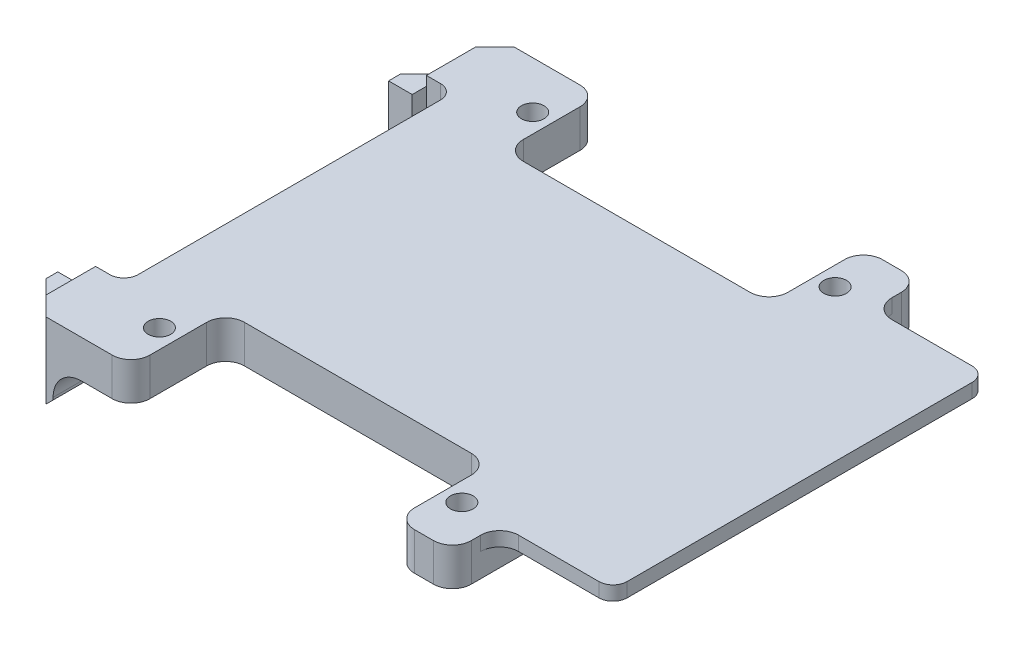
SolidWorks part; units mm, degrees
ref_plane "Front Plane" through (0, 0, 0) normal (0, 0, 1) x (1, 0, 0)
ref_plane "Top Plane" through (0, 0, 0) normal (0, 1, 0) x (1, 0, 0)
ref_plane "Right Plane" through (0, 0, 0) normal (1, 0, 0) x (0, 0, -1)
sketch "Sketch1" plane through (0, 0, 0) normal (0, 0, 1) x (1, 0, 0)
  line L0 (0, 57.0166) -> (0, -12.2536) construction
  line L1 (-45.9137, 0) -> (51.379, 0) construction
  line L2 (-25, 24) -> (32, 24)
  line L3 (-26.5, 17) -> (-25, 17)
  line L4 (-25, 17) -> (-25, 24)
  line L5 (-26.5, 17) -> (-26.5, 15.5)
  line L6 (-26.5, 15.5) -> (-23.5, 15.5)
  line L7 (-23.5, 15.5) -> (-23.5, 22.5)
  line L8 (-23.5, 22.5) -> (32, 22.5)
  line L9 (32, 22.5) -> (32, 24)
  dimension "D1" = 17
  dimension "D2" = 25
  dimension "D3" = 24
  dimension "D4" = 1.5
  dimension "D5" = 1.5
  dimension "D6" = 1.5
  dimension "D7" = 1.5
  dimension "D8" = 32
extrude "Boss-Extrude1" add sketch "Sketch1" along normal mid plane 39.5
sketch "Sketch2" plane through (0, 22.5, 0) normal (0, -1, 0) x (1, 0, 0)
  line L0 (0, -28.7784) -> (0, 29.8663) construction
  line L1 (-38.3762, 0) -> (49.937, 0) construction
  line L2 (-14, 19.75) -> (-14, 14.75)
  line L3 (-23.5, 19.75) -> (32, 19.75) construction
  line L4 (-14, 14.75) -> (14, 14.75)
  line L5 (-14, 19.75) -> (14, 19.75)
  line L6 (14, 19.75) -> (14, 14.75)
  line L7 (14, -19.75) -> (14, -14.75)
  line L8 (-14, -19.75) -> (14, -19.75)
  line L9 (-14, -14.75) -> (14, -14.75)
  line L10 (-14, -19.75) -> (-14, -14.75)
  point P9 (0, -14.75)
  point P12 (0, 19.75)
  point P13 (0, 14.75)
  point P14 (0, -19.75)
  dimension "D1" = 5
  dimension "D2" = 28
extrude "Cut-Extrude1" cut sketch "Sketch2" against normal through all
sketch "Sketch3" plane through (0, 24, 0) normal (0, 1, 0) x (1, 0, 0)
  line L0 (-37.8503, 0) -> (59.1934, 0) construction
  line L1 (0, -32.5682) -> (0, 30.7465) construction
  line L2 (-14, 19.75) -> (-20, 19.75)
  line L3 (-14, 19.75) -> (-25, 19.75) construction
  line L4 (-20, 19.75) -> (-20, 24.75)
  line L5 (-20, 24.75) -> (-14, 24.75)
  line L6 (-14, 24.75) -> (-14, 19.75)
  line L7 (14, 24.75) -> (14, 19.75)
  line L8 (20, 24.75) -> (14, 24.75)
  line L9 (20, 19.75) -> (20, 24.75)
  line L10 (14, 19.75) -> (20, 19.75)
  line L11 (14, -19.75) -> (20, -19.75)
  line L12 (20, -19.75) -> (20, -24.75)
  line L13 (20, -24.75) -> (14, -24.75)
  line L14 (14, -24.75) -> (14, -19.75)
  line L15 (-14, -24.75) -> (-14, -19.75)
  line L16 (-20, -24.75) -> (-14, -24.75)
  line L17 (-20, -19.75) -> (-20, -24.75)
  line L18 (-14, -19.75) -> (-20, -19.75)
  line L19 (17, 24.75) -> (17, 19.75) construction
  circle A0 centre (17, 22.25) radius 1 construction
  circle A1 centre (17, -22.25) radius 1 construction
  circle A2 centre (-17, 22.25) radius 1 construction
  circle A3 centre (-17, -22.25) radius 1 construction
  line M8 (14, -19.75) -> (32, -19.75)
  line M10 (32, 19.75) -> (14, 19.75)
  line M14 (-14, 19.75) -> (-25, 19.75)
  line M16 (-25, -19.75) -> (-14, -19.75)
  dimension "D3" = 2
  dimension "D1" = 5
  dimension "D2" = 6
extrude "Boss-Extrude2" add sketch "Sketch3" against normal blind 4 contours L14 L13 L12 A1 M8 | L17 L16 L15 A3 M16 | L9 L8 L7 A0 M10 | L6 L5 L4 A2 M14
sketch "Sketch4" plane through (0, 22.5, 0) normal (0, -1, 0) x (1, 0, 0)
  line L0 (0, 35.1625) -> (0, -33.0766) construction
  line L1 (-40.0719, 0) -> (51.9068, 0) construction
  line L2 (-20, 20.25) -> (-20, 17.25)
  line L4 (-20, 17.25) -> (-17.5, 17.25)
  line L5 (-17.5, 17.25) -> (-17.5, 20.25)
  line L6 (-17.5, 20.25) -> (-20, 20.25)
  line L7 (17.5, 20.25) -> (20, 20.25)
  line L8 (17.5, 17.25) -> (17.5, 20.25)
  line L9 (20, 17.25) -> (17.5, 17.25)
  line L10 (20, 20.25) -> (20, 17.25)
  line L11 (20, -20.25) -> (20, -17.25)
  line L12 (20, -17.25) -> (17.5, -17.25)
  line L13 (17.5, -17.25) -> (17.5, -20.25)
  line L14 (17.5, -20.25) -> (20, -20.25)
  line L15 (-17.5, -20.25) -> (-20, -20.25)
  line L16 (-17.5, -17.25) -> (-17.5, -20.25)
  line L17 (-20, -17.25) -> (-17.5, -17.25)
  line L18 (-20, -20.25) -> (-20, -17.25)
  line L19 (-23.5, 19.75) -> (-20, 19.75) construction
  line L20 (-14, 24.75) -> (-14, 14.75) construction
  dimension "D1" = 0.5
  dimension "D2" = 3
  dimension "D3" = 2.5
  dimension "D4" = 6
extrude "Boss-Extrude3" [suppressed] add sketch "Sketch4" along normal blind 4
chamfer "Chamfer1" [suppressed] distance 4 angle 45
sketch "Sketch6" plane through (0, 0, -24.75) normal (0, 0, -1) x (-1, 0, 0)
  line L0 (20, 24) -> (25, 24)
  line L1 (20, 20) -> (20, 24) construction
  line L2 (25, 24) -> (25, 15.5)
  line L3 (26.5, 15.5) -> (23.5, 15.5) construction
  line L4 (25, 15.5) -> (23.5, 15.5)
  line L5 (23.5, 15.5) -> (22.25, 16.75)
  line L7 (20, 20) -> (20, 24)
  line L8 (20, 20) -> (19.25, 20)
  line L9 (22.25, 17) -> (22.25, 16.75)
  line L10 (23.5, 15.5) -> (23.5, 22.5) construction
  line L11 (20, 20) -> (14, 20) construction
  arc A0 (19.25, 20) -> (22.25, 17) centre (19.25, 17) cw
  dimension "D3" = 3
  dimension "D1" = 1.25
  dimension "D2" = 45
extrude "Boss-Extrude4" add sketch "Sketch6" against normal up to surface (5 mm away) up to face at (-23.75, 19.75, -19.75)
sketch "Sketch7" plane through (0, 0, 24.75) normal (0, 0, 1) x (1, 0, 0)
  line L0 (-20, 22.5) -> (-20, 24) construction
  line L2 (-20, 20) -> (-20, 24)
  line L4 (-20, 20) -> (-19.25, 20)
  line L7 (-14, 24) -> (-25, 24)
  line L8 (-14, 20) -> (-14, 24)
  line L9 (-20, 24) -> (-25, 24)
  line L10 (-22.25, 16.75) -> (-22.25, 17)
  line L11 (-23.5, 15.5) -> (-22.25, 16.75)
  line L12 (-25, 15.5) -> (-23.5, 15.5)
  line L13 (-25, 24) -> (-25, 15.5)
  line L17 (-22.25, 16.75) -> (-22.25, 17)
  line L18 (-23.5, 15.5) -> (-22.25, 16.75)
  line L19 (-25, 15.5) -> (-23.5, 15.5)
  line L20 (-25, 24) -> (-25, 15.5)
  line L21 (-19.25, 20) -> (-14, 20)
  arc A1 (-19.25, 20) -> (-22.25, 17) centre (-19.25, 17) ccw
  arc A2 (-19.25, 20) -> (-22.25, 17) centre (-19.25, 17) ccw
  dimension "D1" = 0
extrude "Boss-Extrude5" add sketch "Sketch7" against normal up to surface (5 mm away) up to face at (-23.75, 19.75, 19.75)
chamfer "Chamfer2" distance 2 angle 45 2 edges at (-25, 19.75, -24.75) (-25, 19.75, 24.75)
fillet "Fillet1" radius 2 12 edges at (20, 23.25, -19.75) (14, 22, -24.75) (20, 22, -24.75) (-14, 22, -24.75) (14, 22, 24.75) (20, 22, 24.75) (20, 23.25, 19.75) (-14, 22, 24.75) (-14, 23.25, 14.75) (14, 23.25, 14.75) (14, 23.25, -14.75) (-14, 23.25, -14.75)
sketch "Sketch8" plane through (0, 24, 0) normal (0, 1, 0) x (1, 0, 0)
  line L0 (-29.245, 0) -> (51.3108, 0) construction
  line L1 (-25, 17.5) -> (-22, 17.5)
  line L2 (-25, -19.75) -> (-25, 19.75) construction
  line L3 (-22, 17.5) -> (-22, -17.5)
  line L4 (-25, 17.5) -> (-25, -17.5) construction
  line L5 (-25, -22.75) -> (-25, 22.75) construction
  line L6 (-25, -17.5) -> (-22, -17.5)
  line L7 (-25, 17.5) -> (-26.8679, 17.5)
  line L8 (-26.8679, 17.5) -> (-26.8679, -17.5)
  line L9 (-25, -17.5) -> (-26.8679, -17.5)
  point P12 (-25, 0)
  point P13 (-22, 0)
  point P16 (-26.8679, 0)
  dimension "D1" = 3
  dimension "D2" = 35
extrude "Cut-Extrude3" cut sketch "Sketch8" against normal through all
sketch "Sketch9" plane through (0, 15.5, 0) normal (0, -1, 0) x (1, 0, 0)
  line L0 (-33.3175, 0) -> (50.3175, 0) construction
  line L1 (-25, 22.75) -> (-29, 18.75)
  line L2 (-29, 18.75) -> (-29, 17.5)
  line L3 (-29, 17.5) -> (-26.5, 17.5)
  line L4 (-26.5, 17.5) -> (-26.5, 20.5)
  line L5 (-26.5, 20.5) -> (-25, 20.5)
  line L6 (-25, 20.5) -> (-25, 22.75)
  line L7 (-23.5, 24.25) -> (-25, 22.75) construction
  line L8 (-25, -20.5) -> (-25, -22.75)
  line L9 (-26.5, -20.5) -> (-25, -20.5)
  line L10 (-26.5, -17.5) -> (-26.5, -20.5)
  line L11 (-29, -17.5) -> (-26.5, -17.5)
  line L12 (-29, -18.75) -> (-29, -17.5)
  line L13 (-25, -22.75) -> (-29, -18.75)
  dimension "D1" = 2.5
  dimension "D2" = 41
extrude "Boss-Extrude6" add sketch "Sketch9" against normal blind 6
fillet "Fillet2" radius 1.5 2 edges at (-25, 21.5, 21.625) (-25, 21.5, -21.625)
sketch "Sketch10" [suppressed] plane through (0, 20, 0) normal (0, -1, 0) x (1, 0, 0)
  line L0 (63.4148, 0) -> (-38.9985, 0) construction
  line L1 (17.5, 19.75) -> (17.5, 20.25)
  line L2 (17.5, 20.25) -> (-17.5, 20.25)
  line L3 (-17.5, 20.25) -> (-20, 20.25) construction
  line L4 (-17.5, 20.25) -> (-17.5, 19.75)
  line L5 (-17.5, 19.75) -> (-14, 19.75) construction
  line L6 (-17.5, 19.75) -> (17.5, 19.75)
  line L7 (-17.5, 17.25) -> (-17.5, 20.25) construction
  line L8 (-17.5, -19.75) -> (17.5, -19.75)
  line L9 (-17.5, -20.25) -> (-17.5, -19.75)
  line L10 (17.5, -20.25) -> (-17.5, -20.25)
  line L11 (17.5, -19.75) -> (17.5, -20.25)
extrude "Cut-Extrude4" [suppressed] cut sketch "Sketch10" against normal up to surface (2.5 mm away)
sketch "Sketch11" plane through (0, 22.5, 0) normal (0, -1, 0) x (1, 0, 0)
  line L0 (0, 18.2681) -> (0, -19.6476) construction
  line L1 (-10, 0) -> (10, 0) construction
  circle A2 centre (10, 0) radius 2.5
  circle A4 centre (10, 0) radius 1
  circle A6 centre (-10, 0) radius 2.5
  circle A8 centre (-10, 0) radius 1
  dimension "D1" = 20
extrude "Boss-Extrude7" add sketch "Sketch11" along normal blind 10.5
sketch "Sketch12" plane through (0, 22.5, 0) normal (0, -1, 0) x (1, 0, 0)
  circle A2 centre (3.5, 8.2) radius 2
extrude "Cut-Extrude5" [suppressed] cut sketch "Sketch12" against normal through all
fillet "Fillet3" radius 1 2 edges at (10, 22.5, 2.5) (-10, 22.5, 2.5)
fillet "Fillet4" radius 1.5 4 edges at (32, 23.25, -19.75) (32, 23.25, 19.75) (-22, 23.25, -17.5) (-22, 23.25, 17.5)
sketch "Sketch13" plane through (0, 22.5, 0) normal (0, -1, 0) x (1, 0, 0)
  line L0 (0, 23.5867) -> (0, -26.9118) construction
  line L1 (-32.7011, 0) -> (42.0296, 0) construction
  line L2 (14, 19.75) -> (14, 12.75)
  line L3 (14, 12.75) -> (20, 12.75)
  line L4 (20, 12.75) -> (20, 19.75)
  line L5 (20, 19.75) -> (14, 19.75)
  line L6 (18, 24.75) -> (16, 24.75) construction
  line L7 (20, -19.75) -> (14, -19.75)
  line L8 (20, -12.75) -> (20, -19.75)
  line L9 (14, -12.75) -> (20, -12.75)
  line L10 (14, -19.75) -> (14, -12.75)
  line L11 (-14, -19.75) -> (-14, -12.75)
  line L12 (-14, -12.75) -> (-20, -12.75)
  line L13 (-20, -12.75) -> (-20, -19.75)
  line L14 (-20, -19.75) -> (-14, -19.75)
  line L15 (-20, 19.75) -> (-14, 19.75)
  line L16 (-20, 12.75) -> (-20, 19.75)
  line L17 (-14, 12.75) -> (-20, 12.75)
  line L18 (-14, 19.75) -> (-14, 12.75)
  dimension "D1" = 12
extrude "Boss-Extrude8" add sketch "Sketch13" along normal up to surface (2.5 mm away) up to face at (17, 20, 22.5547)
sketch "Sketch14" plane through (0, 20, 0) normal (0, -1, 0) x (1, 0, 0)
  line L0 (0, 37.6134) -> (0, -29.6142) construction
  line L1 (-42.0703, 0) -> (38.0923, 0) construction
  line L2 (18, 24.75) -> (16, 24.75) construction
  circle A0 centre (16, 19.75) radius 1.2
  circle A1 centre (-16, 19.75) radius 1.2
  circle A2 centre (-16, -19.75) radius 1.2
  circle A3 centre (16, -19.75) radius 1.2
  dimension "D2" = 2.4
  dimension "D1" = 5
  dimension "D3" = 32
extrude "Cut-Extrude6" cut sketch "Sketch14" against normal through all
sketch "Sketch15" plane through (0, 22.5, 0) normal (0, -1, 0) x (1, 0, 0)
  line L0 (14, 16.75) -> (14, 12.75) construction
  line L1 (-12, 14.75) -> (12, 14.75) construction
  line L2 (-14, 12.75) -> (-14, 16.75) construction
  line L3 (14, 16.75) -> (14, 12.75)
  line L4 (-12, 14.75) -> (12, 14.75)
  line L5 (-14, 12.75) -> (-14, 16.75)
  line L6 (-14, 12.75) -> (14, 12.75)
  line L7 (-28.3552, 0) -> (39.9172, 0) construction
  line L8 (-14, -12.75) -> (14, -12.75)
  line L9 (-14, -12.75) -> (-14, -16.75)
  line L10 (-12, -14.75) -> (12, -14.75)
  line L11 (14, -16.75) -> (14, -12.75)
  arc A0 (12, 14.75) -> (14, 16.75) centre (12, 16.75) ccw construction
  arc A1 (-14, 16.75) -> (-12, 14.75) centre (-12, 16.75) ccw construction
  arc A2 (12, 14.75) -> (14, 16.75) centre (12, 16.75) ccw
  arc A3 (-14, 16.75) -> (-12, 14.75) centre (-12, 16.75) ccw
  arc A4 (-14, -16.75) -> (-12, -14.75) centre (-12, -16.75) cw
  arc A5 (12, -14.75) -> (14, -16.75) centre (12, -16.75) cw
extrude "Boss-Extrude9" add sketch "Sketch15" along normal up to surface (2.5 mm away) up to face at (-17.2, 20, 19.75)
fillet "Fillet5" radius 2 4 edges at (-20, 21.25, -12.75) (20, 21.25, -12.75) (20, 21.25, 12.75) (-20, 21.25, 12.75)
sketch "Sketch16" plane through (0, 15.5, 0) normal (0, -1, 0) x (1, 0, 0)
  line L0 (-23.5, 17.5) -> (-23.5, 21.5)
  line L1 (-23.5, 19.75) -> (-23.5, 24.25) construction
  line L2 (-23.5, 21.5) -> (-20, 21.5)
  line L3 (-20, 21.5) -> (-20, 17.5)
  line L4 (-20, 14.75) -> (-20, 19.75) construction
  line L5 (-20, 17.5) -> (-23.5, 17.5)
  line L6 (-44.9233, 0) -> (38.3373, 0) construction
  line L7 (-20, -17.5) -> (-23.5, -17.5)
  line L8 (-20, -21.5) -> (-20, -17.5)
  line L9 (-23.5, -21.5) -> (-20, -21.5)
  line L10 (-23.5, -17.5) -> (-23.5, -21.5)
  dimension "D1" = 4
extrude "Cut-Extrude7" [suppressed] cut sketch "Sketch16" against normal up to surface (7 mm away)
sketch "Sketch18" plane through (0, 0, 19.75) normal (0, 0, 1) x (1, 0, 0)
  line L4 (-26.5, 15.5) -> (-25, 15.5)
  line L6 (-26.5, 15.5) -> (-25, 15.5)
  line L12 (-25, 15.5) -> (-25, 17)
  line L14 (-25, 15.5) -> (-25, 17)
  line L16 (-25, 17) -> (-26.5, 17)
  line L17 (-25, 17) -> (-26.5, 17)
  line L18 (-26.5, 17) -> (-26.5, 15.5)
  line L19 (-26.5, 17) -> (-26.5, 15.5)
  dimension "D1" = 0
extrude "Boss-Extrude10" add sketch "Sketch18" along normal up to surface (0.75 mm away) up to face at (-25.6723, 18.7973, 20.5)
sketch "Sketch19" plane through (0, 0, -19.75) normal (0, 0, -1) x (-1, 0, 0)
  line L4 (25, 17) -> (25, 15.5)
  line L6 (25, 17) -> (25, 15.5)
  line L12 (25, 15.5) -> (26.5, 15.5)
  line L14 (25, 15.5) -> (26.5, 15.5)
  line L16 (26.5, 15.5) -> (26.5, 17)
  line L17 (26.5, 15.5) -> (26.5, 17)
  line L18 (26.5, 17) -> (25, 17)
  line L19 (26.5, 17) -> (25, 17)
  dimension "D1" = 0
extrude "Boss-Extrude11" add sketch "Sketch19" along normal up to surface (0.75 mm away) up to face at (-25.6723, 18.7973, -20.5)
